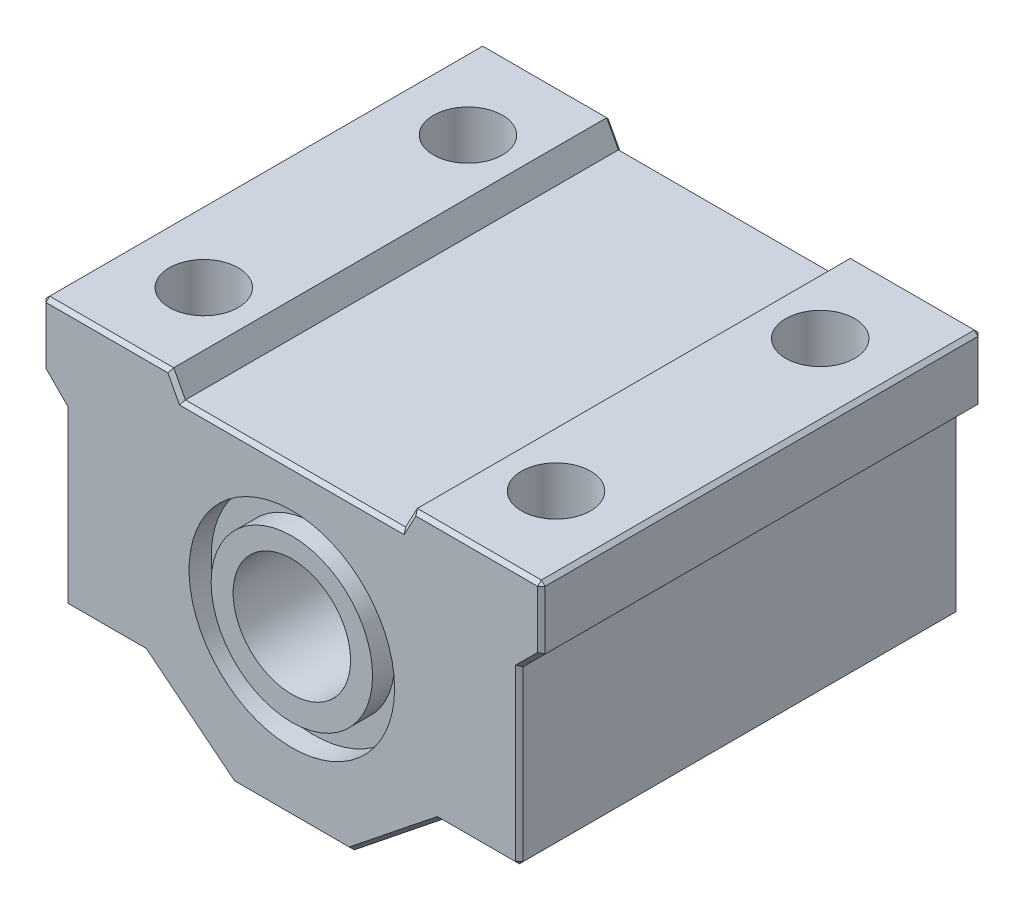
SolidWorks part; units mm, degrees
ref_plane "Front" through (0, 0, 0) normal (0, 0, 1) x (1, 0, 0)
ref_plane "Top" through (0, 0, 0) normal (0, 1, 0) x (1, 0, 0)
ref_plane "Right" through (0, 0, 0) normal (1, 0, 0) x (0, 0, -1)
sketch "Croquis1" plane through (0, 0, 0) normal (0, 0, 1) x (1, 0, 0)
  line L0 (23.9725, -11.15) -> (17, -11.15) construction
  line L1 (-4, -11.15) -> (4, -11.15)
  line L2 (-17, 6.9) -> (-17, 11.15)
  line L3 (-17, 11.15) -> (-10, 11.15)
  line L4 (17, 6.9) -> (17, 11.15)
  line L5 (-17, -11.15) -> (17, 11.15) construction
  line L6 (-17, 11.15) -> (17, -11.15) construction
  line L7 (23.9725, -6.35) -> (17, -6.35) construction
  line L8 (0, 15.7494) -> (0, -21.8819) construction
  line L9 (4, 15.7494) -> (4, -21.8819) construction
  line L10 (-4, 15.7494) -> (-4, -21.8819) construction
  line L11 (-10, 15.7494) -> (-10, -20.07) construction
  line L12 (10, 15.7494) -> (10, -20.07) construction
  line L13 (-10, -6.35) -> (-4, -11.15)
  line L14 (-10, -6.35) -> (-15.5, -6.35)
  line L15 (4, -11.15) -> (10, -6.35)
  line L16 (10, -6.35) -> (15.5, -6.35)
  line L17 (-17, -11.15) -> (-24.8088, -11.15) construction
  line L18 (4, -11.15) -> (-4, -11.15) construction
  line L19 (-18.2154, 9.65) -> (20.4266, 9.65) construction
  line L20 (-10, 11.15) -> (-7.5, 9.65)
  line L21 (10, 11.15) -> (7.5, 9.65)
  line L22 (7.5, 9.65) -> (-7.5, 9.65)
  line L23 (10, 11.15) -> (17, 11.15)
  line L24 (-19.1796, 6.9) -> (21.02, 6.9) construction
  line L25 (-19.1796, 5.4) -> (19.0968, 5.4) construction
  line L26 (-17, 6.9) -> (-15.5, 5.4)
  line L27 (-15.5, 5.4) -> (-15.5, -6.35)
  line L28 (17, 6.9) -> (15.5, 5.4)
  line L29 (15.5, 5.4) -> (15.5, -6.35)
  line L30 (15.5, -6.35) -> (-15.5, -6.35) construction
  point P0 (0, 0)
  dimension "D1" = 22.3
  dimension "D2" = 34
  dimension "D3" = 17.5
  dimension "D4" = 4
  dimension "D5" = 4
  dimension "D6" = 10
  dimension "D7" = 10
  dimension "D8" = 1.5
  dimension "D9" = 8.5
  dimension "D10" = 1.5
  dimension "D11" = 7
  dimension "D12" = 9.5
  dimension "D13" = 7
extrude "Saliente-Extruir1" add sketch "Croquis1" along normal mid plane 30
sketch "Croquis2" plane through (0, 0, 15) normal (0, 0, 1) x (1, 0, 0)
  line L0 (-19.8575, 0.15) -> (20.6235, 0.15) construction
  line L1 (17, 11.15) -> (10, 11.15) construction
  line L2 (0, 9.65) -> (0, -14.2159) construction
  line L3 (7.5, 9.65) -> (-7.5, 9.65) construction
  circle A0 centre (0, 0.15) radius 4
  dimension "D2" = 8
  dimension "D1" = 11
extrude "Cortar-Extruir1" cut sketch "Croquis2" against normal through all
sketch "Croquis3" plane through (0, 11.15, 0) normal (0, 1, 0) x (1, 0, 0)
  line L0 (17, -15) -> (17, 15) construction
  line L1 (-17, -15) -> (-17, 15) construction
  line L2 (-10, -15) -> (-17, -15) construction
  line L3 (17, 15) -> (10, 15) construction
  circle A0 centre (-12, 9) radius 2
  circle A1 centre (12, 9) radius 2
  circle A2 centre (-12, -9) radius 2
  circle A3 centre (12, -9) radius 2
  dimension "D7" = 4
  dimension "D8" = 4
  dimension "D9" = 4
  dimension "D10" = 4
  dimension "D1" = 24
  dimension "D2" = 5
  dimension "D3" = 24
  dimension "D4" = 5
  dimension "D5" = 18
  dimension "D6" = 6
  dimension "D11" = 18
  dimension "D12" = 6
extrude "Cortar-Extruir2" cut sketch "Croquis3" against normal through all both and the other way through all
sketch "Croquis4" plane through (0, 0, 15) normal (0, 0, 1) x (1, 0, 0)
  line L0 (-10, 11.15) -> (-7.5, 9.65)
  line L1 (-7.5, 9.65) -> (-8.3, 11.15)
  line L2 (-8.3, 11.15) -> (-10, 11.15)
  line L3 (7.5, 9.65) -> (10, 11.15)
  line L4 (7.5, 9.65) -> (8.3, 11.15)
  line L5 (8.3, 11.15) -> (10, 11.15)
  dimension "D1" = 8.3
extrude "Saliente-Extruir2" add sketch "Croquis4" against normal through all
sketch "Croquis5" plane through (0, 0, 15) normal (0, 0, 1) x (1, 0, 0)
  circle A0 centre (0, 0) radius 5.5
  circle A1 centre (0, 0) radius 7
  dimension "D1" = 11
  dimension "D2" = 14
extrude "Cortar-Extruir3" cut sketch "Croquis5" against normal blind 1.5
sketch "Croquis6" plane through (0, 0, -15) normal (0, 0, -1) x (-1, 0, 0)
  circle A0 centre (0, 0) radius 5.5
  circle A1 centre (0, 0) radius 7
  dimension "D1" = 11
  dimension "D2" = 14
extrude "Cortar-Extruir4" cut sketch "Croquis6" against normal blind 1.5
sketch "Croquis7" plane through (0, 11.15, 0) normal (0, 1, 0) x (1, 0, 0)
  circle A0 centre (-12, 9) radius 2.35
  circle A1 centre (-12, -9) radius 2.35
  circle A2 centre (12, -9) radius 2.35
  circle A3 centre (12, 9) radius 2.35
  dimension "D1" = 4.7
extrude "Cortar-Extruir5" cut sketch "Croquis7" against normal blind 8.5
chamfer "Chaflán1" distance 0.25 angle 45 37 edges at (0, 9.65, 15) (-7, 0, -15) (17, 9.025, -15) (16.25, 6.15, -15) (15.5, -0.475, -15) (12.75, -6.35, -15) (7, -8.75, -15) (-12.65, 11.15, 15) (0, -11.15, -15) (-7, -8.75, -15) (-12.75, -6.35, -15) (-15.5, -0.475, -15) (-16.25, 6.15, -15) (-17, 9.025, -15) (-12.65, 11.15, -15) (-17, 9.025, 15) (0, 9.65, -15) (12.65, 11.15, -15) (-16.25, 6.15, 15) (-15.5, -0.475, 15) (17, 11.15, 0) (15.5, -6.35, 0) (-15.5, -6.35, 0) (-17, 11.15, 0) (-12.75, -6.35, 15) (-7, -8.75, 15) (0, -11.15, 15) (7, -8.75, 15) (12.65, 11.15, 15) (12.75, -6.35, 15) (15.5, -0.475, 15) (16.25, 6.15, 15) (17, 9.025, 15) (-7.9, 10.4, -15) (-7.9, 10.4, 15) (7.9, 10.4, -15) (7.9, 10.4, 15)
